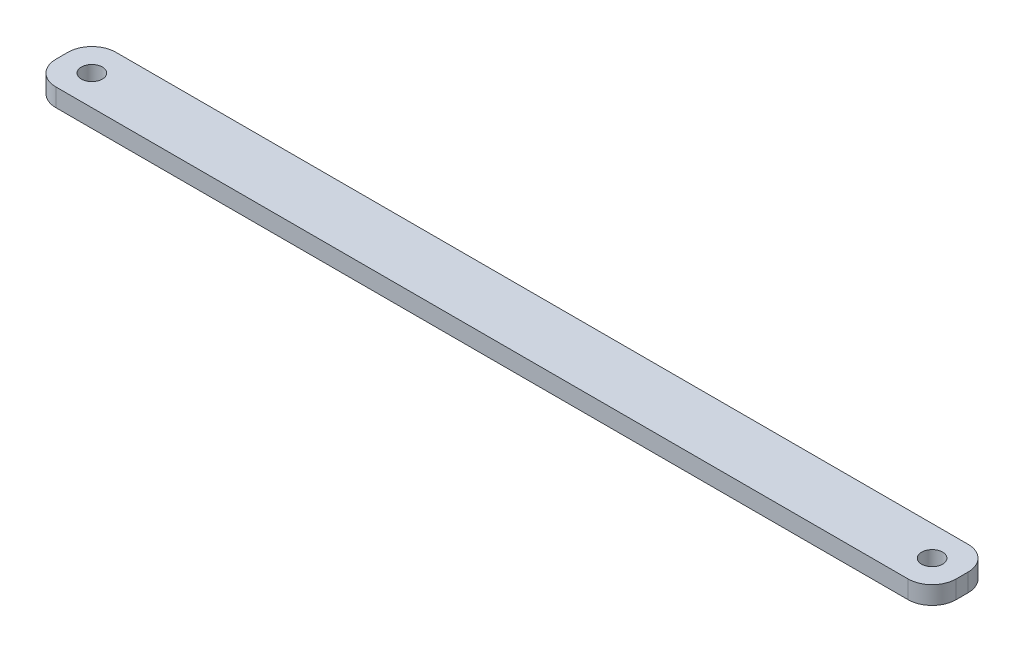
SolidWorks part; units mm, degrees
ref_plane "Front Plane" through (0, 0, 0) normal (0, 0, 1) x (1, 0, 0)
ref_plane "Top Plane" through (0, 0, 0) normal (0, 1, 0) x (1, 0, 0)
ref_plane "Right Plane" through (0, 0, 0) normal (1, 0, 0) x (0, 0, -1)
sketch "Sketch1" plane through (0, 0, 0) normal (0, 1, 0) x (1, 0, 0)
  line L1 (-75, 5) -> (75, 5)
  line L2 (-75, 5) -> (-75, -5)
  line L3 (-75, -5) -> (75, -5)
  line L4 (75, 5) -> (75, -5)
  line L5 (-75, 5) -> (75, -5) construction
  line L6 (-75, -5) -> (75, 5) construction
  point P0 (0, 0)
  dimension "D1" = 10
  dimension "D2" = 150
extrude "Boss-Extrude1" add sketch "Sketch1" along normal blind 3
fillet "Fillet1" radius 4 4 edges at (-75, 1.5, -5) (-75, 1.5, 5) (75, 1.5, -5) (75, 1.5, 5)
sketch "Sketch4" plane through (0, 3, 0) normal (0, 1, 0) x (1, 0, 0)
  line L0 (-70, 0) -> (70, 0) construction
  circle A0 centre (-70, 0) radius 1.75
  circle A1 centre (70, 0) radius 1.75
  point P4 (0, 0)
  dimension "D2" = 3.5
  dimension "D3" = 3.5
  dimension "D1" = 140
extrude "Cut-Extrude1" cut sketch "Sketch4" against normal through all
